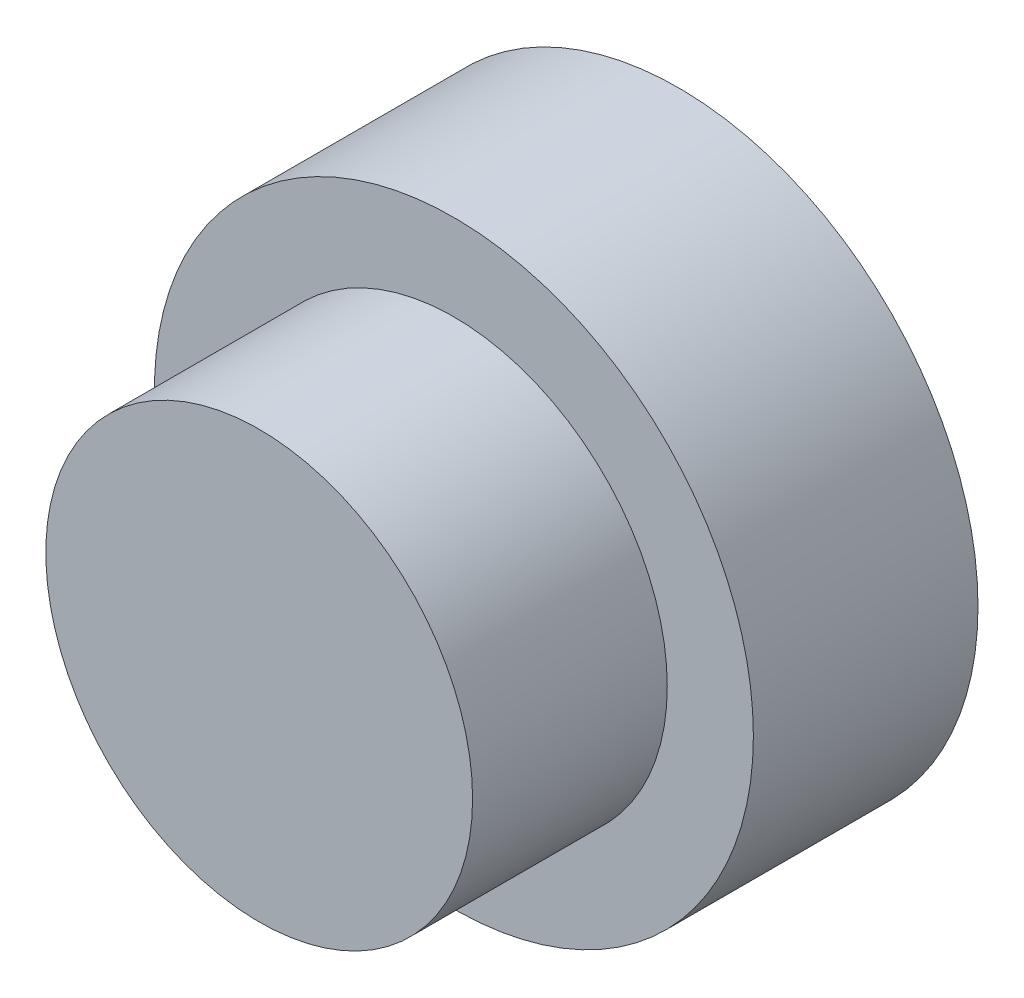
SolidWorks part; units mm, degrees
ref_plane "Płaszczyzna przednia" through (0, 0, 0) normal (0, 0, 1) x (1, 0, 0)
ref_plane "Płaszczyzna górna" through (0, 0, 0) normal (0, 1, 0) x (1, 0, 0)
ref_plane "Płaszczyzna prawa" through (0, 0, 0) normal (1, 0, 0) x (0, 0, -1)
sketch "Szkic1" plane through (0, 0, 0) normal (0, 0, 1) x (1, 0, 0)
  circle A0 centre (1040.4515, -43.5323) radius 4
  dimension "D1" = 8
extrude "Dodanie-wyciągnięcie1" add sketch "Szkic1" along normal blind 3
sketch "Szkic2" plane through (0, 0, 3) normal (0, 0, 1) x (1, 0, 0)
  circle A0 centre (1040.4515, -43.5323) radius 2.85
  circle A1 centre (1040.4515, -43.5323) radius 4 construction
  dimension "D1" = 5.7
  dimension "D2" = 0
extrude "Dodanie-wyciągnięcie2" add sketch "Szkic2" along normal blind 2.6
